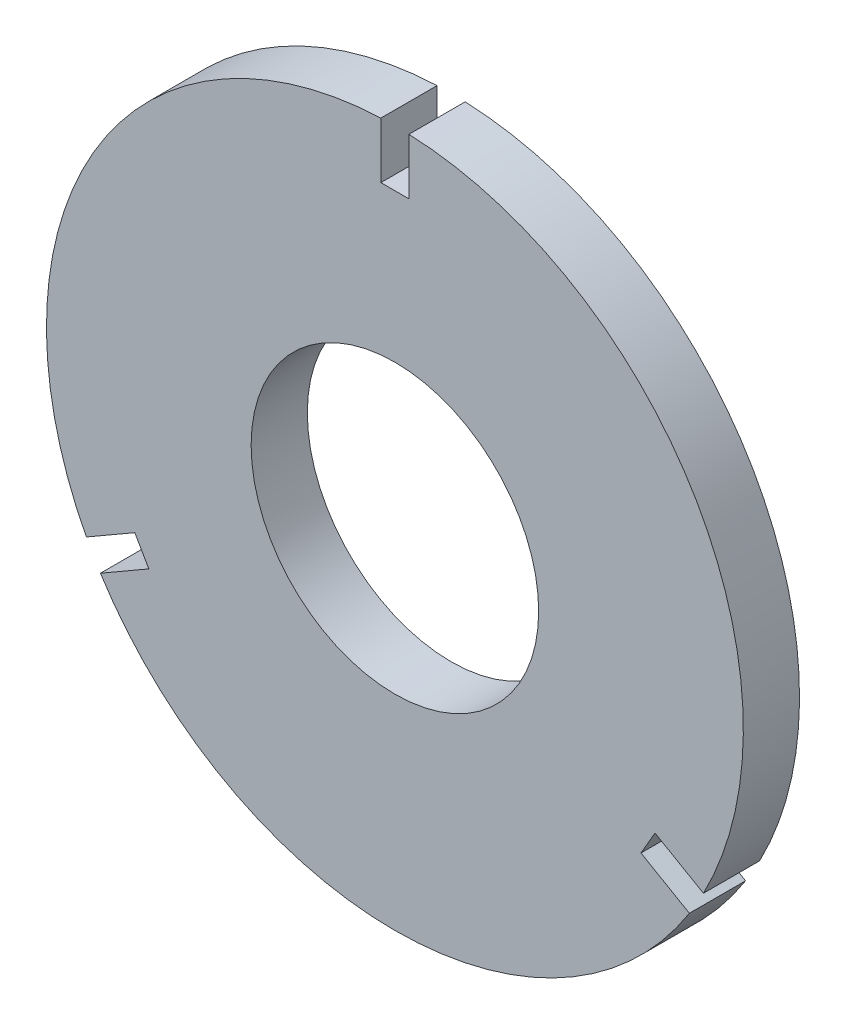
SolidWorks part; units mm, degrees
ref_plane "Front Plane" through (0, 0, 0) normal (0, 0, 1) x (1, 0, 0)
ref_plane "Top Plane" through (0, 0, 0) normal (0, 1, 0) x (1, 0, 0)
ref_plane "Right Plane" through (0, 0, 0) normal (1, 0, 0) x (0, 0, -1)
sketch "Sketch2" plane through (0, 0, 0) normal (0, 0, 1) x (1, 0, 0)
  circle A0 centre (0, 0) radius 15.35
  circle A1 centre (0, 0) radius 37.2
  dimension "D1" = 30.7
  dimension "D2" = 74.4
extrude "Boss-Extrude1" add sketch "Sketch2" along normal blind 6
sketch "Sketch3" plane through (0, 0, 6) normal (0, 0, 1) x (1, 0, 0)
  line L0 (0, 0) -> (0, 58.7932) construction
  line L1 (1.5, 37.2) -> (-1.5, 37.2)
  line L2 (-1.5, 37.2) -> (-1.5, 31.2)
  line L3 (-1.5, 31.2) -> (1.5, 31.2)
  line L4 (1.5, 31.2) -> (1.5, 37.2)
  line L5 (26.27, -16.899) -> (31.4661, -19.899)
  line L6 (31.4661, -19.899) -> (32.9661, -17.301)
  line L7 (32.9661, -17.301) -> (27.77, -14.301)
  line L8 (27.77, -14.301) -> (26.27, -16.899)
  line L9 (-27.77, -14.301) -> (-32.9661, -17.301)
  line L10 (-32.9661, -17.301) -> (-31.4661, -19.899)
  line L11 (-31.4661, -19.899) -> (-26.27, -16.899)
  line L12 (-26.27, -16.899) -> (-27.77, -14.301)
  circle A1 centre (0, 0) radius 37.2 construction
  point P6 (0, 37.2)
  point P18 (0, 0)
  dimension "D1" = 3
  dimension "D2" = 6
  dimension "D3" = 3
extrude "Cut-Extrude1" cut sketch "Sketch3" against normal blind 6
